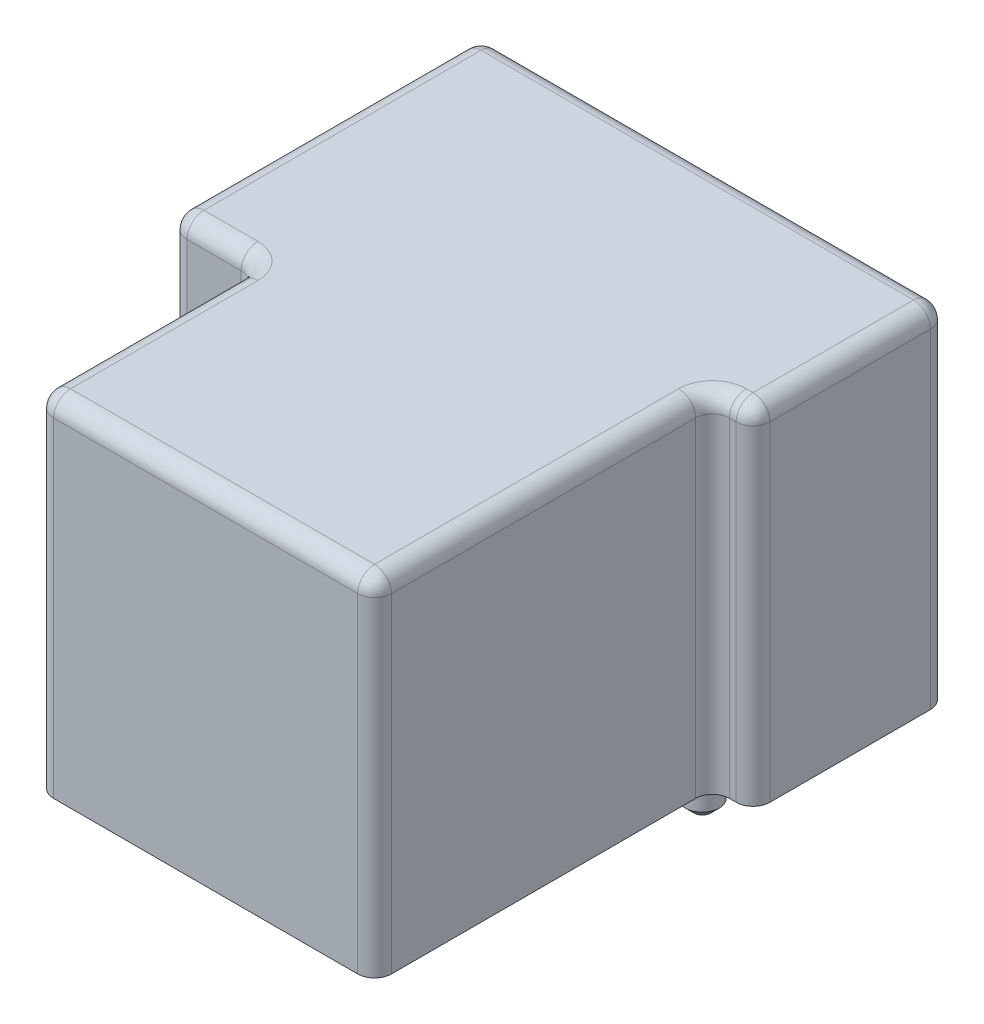
SolidWorks part; units mm, degrees
ref_plane "Front Plane" through (0, 0, 0) normal (0, 0, 1) x (1, 0, 0)
ref_plane "Top Plane" through (0, 0, 0) normal (0, 1, 0) x (1, 0, 0)
ref_plane "Right Plane" through (0, 0, 0) normal (1, 0, 0) x (0, 0, -1)
sketch "Sketch1" plane through (0, 0, 0) normal (0, 1, 0) x (1, 0, 0)
  line L0 (0, 1) -> (0, 12.1)
  line L1 (-1, 13.1) -> (-4.2, 13.1)
  line L2 (-5.2, 14.1) -> (-5.2, 30.5)
  line L3 (-4.2, 31.5) -> (21.4, 31.5)
  line L4 (22.4, 30.5) -> (22.4, 21)
  line L5 (21.4, 20) -> (21, 20)
  line L6 (20, 19) -> (20, 1)
  line L7 (19, 0) -> (1, 0)
  arc A0 (21.4, 31.5) -> (22.4, 30.5) centre (21.4, 30.5) cw
  arc A1 (21, 20) -> (20, 19) centre (21, 19) ccw
  arc A2 (22.4, 21) -> (21.4, 20) centre (21.4, 21) cw
  arc A3 (20, 1) -> (19, 0) centre (19, 1) cw
  arc A4 (0, 1) -> (1, 0) centre (1, 1) ccw
  arc A5 (0, 12.1) -> (-1, 13.1) centre (-1, 12.1) ccw
  arc A6 (-4.2, 13.1) -> (-5.2, 14.1) centre (-4.2, 14.1) cw
  arc A7 (-5.2, 30.5) -> (-4.2, 31.5) centre (-4.2, 30.5) cw
  point P11 (22.4, 31.5)
  point P16 (22.4, 20)
  point P19 (20, 0)
  point P22 (0, 0)
  point P27 (-5.2, 13.1)
  point P30 (-5.2, 31.5)
  dimension "D7" = 1
  dimension "D1" = 20
  dimension "D2" = 25.2
  dimension "D3" = 27.6
  dimension "D4" = 11.5
  dimension "D5" = 31.5
  dimension "D6" = 18.4
extrude "Boss-Extrude1" add sketch "Sketch1" along normal blind 20.5
fillet "Fillet1" radius 1 16 edges at (22.4, 20.5, -25.75) (22.1071, 20.5, -20.2929) (21.2, 20.5, -20) (20.2929, 20.5, -19.7071) (20, 20.5, -10) (19.7071, 20.5, -0.2929) (10, 20.5, 0) (0.2929, 20.5, -0.2929) (0, 20.5, -6.55) (-0.2929, 20.5, -12.8071) (-2.6, 20.5, -13.1) (-4.9071, 20.5, -13.3929) (-5.2, 20.5, -22.3) (-4.9071, 20.5, -31.2071) (8.6, 20.5, -31.5) (22.1071, 20.5, -31.2071)
sketch "Sketch2" plane through (0, 0, 0) normal (0, -1, 0) x (1, 0, 0)
  line L0 (21.4, -31.5) -> (-4.2, -31.5) construction
  line L1 (22.4, -21) -> (22.4, -30.5) construction
  circle A0 centre (13.7, -6.5) radius 0.5
  circle A1 centre (3.5, -6.5) radius 0.5
  circle A2 centre (17.5, -21.9) radius 1
  circle A3 centre (17.5, -29.6) radius 1
  circle A4 centre (-0.3, -19.36) radius 1
  point P10 (0, 0)
  point P11 (0, 0)
  point P12 (3.2973, -4.2859)
  dimension "D1" = 1
  dimension "D2" = 2
  dimension "D9" = 1.9
  dimension "D10" = 4.9
  dimension "D3" = 7.7
  dimension "D4" = 15.4
  dimension "D5" = 10.2
  dimension "D6" = 3.8
  dimension "D7" = 17.8
  dimension "D8" = 2.54
extrude "Boss-Extrude2" add sketch "Sketch2" along normal blind 3.2
chamfer "Chamfer1" distance 0.5 angle 45 5 edges at (17.5, -3.2, -30.6) (17.5, -3.2, -22.9) (13.7, -3.2, -7) (3.5, -3.2, -7) (-0.3, -3.2, -20.36)
